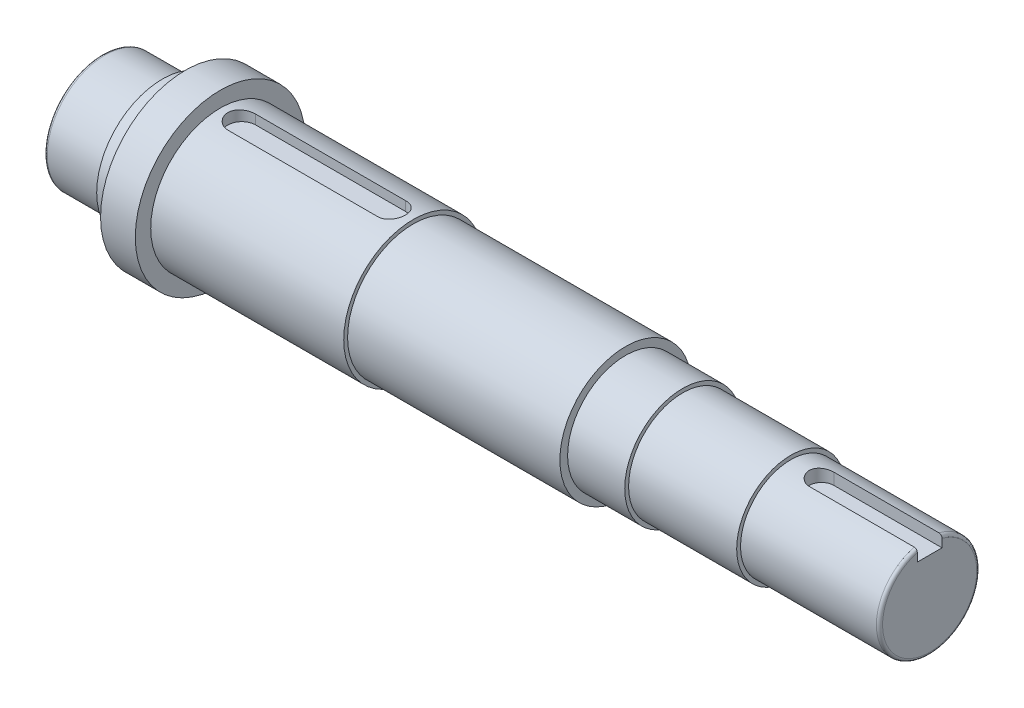
SolidWorks part; units mm, degrees
material "Plain Carbon Steel"
ref_plane "Front Plane" through (0, 0, 0) normal (0, 0, 1) x (1, 0, 0)
ref_plane "Top Plane" through (0, 0, 0) normal (0, 1, 0) x (1, 0, 0)
ref_plane "Right Plane" through (0, 0, 0) normal (1, 0, 0) x (0, 0, -1)
sketch "Sketch1" plane through (0, 0, 0) normal (0, 0, 1) x (1, 0, 0)
  line L0 (-305.229, 0) -> (230.771, 0) construction
  line L1 (-305.229, 0) -> (-305.229, 37.5)
  line L2 (-305.229, 37.5) -> (-266.229, 37.5)
  line L3 (-266.229, 37.5) -> (-266.229, 42.5)
  line L4 (-266.229, 42.5) -> (-251.229, 42.5)
  line L5 (-251.229, 42.5) -> (-251.229, 55)
  line L6 (-251.229, 55) -> (-228.729, 55)
  line L7 (-228.729, 55) -> (-228.729, 45)
  line L8 (-228.729, 45) -> (-103.729, 45)
  line L9 (-103.729, 45) -> (-103.729, 42.5)
  line L10 (-103.729, 42.5) -> (33.771, 42.5)
  line L11 (33.771, 42.5) -> (33.771, 37.5)
  line L12 (33.771, 37.5) -> (70.771, 37.5)
  line L13 (70.771, 37.5) -> (70.771, 35)
  line L14 (70.771, 35) -> (140.771, 35)
  line L15 (140.771, 35) -> (140.771, 32.5)
  line L16 (140.771, 32.5) -> (230.771, 32.5)
  line L17 (230.771, 32.5) -> (230.771, 0)
  line L18 (-305.229, 0) -> (230.771, 0)
  dimension "D1" = 75
  dimension "D2" = 85
  dimension "D3" = 110
  dimension "D4" = 90
  dimension "D5" = 85
  dimension "D6" = 75
  dimension "D7" = 70
  dimension "D8" = 65
  dimension "D9" = 39
  dimension "D10" = 15
  dimension "D11" = 22.5
  dimension "D12" = 125
  dimension "D13" = 137.5
  dimension "D14" = 37
  dimension "D15" = 70
  dimension "D16" = 90
  dimension "D17" = 305.229
  dimension "D18" = 536
revolve "Revolve1" add sketch "Sketch1" angle 360 about L0
fillet "Fillet1" radius 2 2 edges at (230.771, 0, 32.5) (-305.229, 0, 37.5)
ref_plane "Plane1" through (0, 45, 0) normal (0, 1, 0) x (1, 0, 0)
ref_plane "Plane2" through (0, 32.5, 0) normal (0, 1, 0) x (1, 0, 0)
sketch "Sketch2" plane through (0, 45, 0) normal (0, 1, 0) x (1, 0, 0)
  line L0 (-214.729, 0) -> (-117.729, 0) construction
  line L1 (-214.729, 9) -> (-117.729, 9)
  line L2 (-214.729, -9) -> (-117.729, -9)
  line L3 (-103.729, -45) -> (-103.729, 45) construction
  arc A0 (-214.729, 9) -> (-214.729, -9) centre (-214.729, 0) ccw
  arc A1 (-117.729, -9) -> (-117.729, 9) centre (-117.729, 0) ccw
  point P3 (-166.229, 0)
  dimension "D3" = 9
  dimension "D1" = 62.5
  dimension "D2" = 97
extrude "Cut-Extrude1" cut sketch "Sketch2" against normal blind 7
sketch "Sketch3" plane through (0, 32.5, 0) normal (0, 1, 0) x (1, 0, 0)
  line L0 (160.771, 0) -> (239.6722, 0) construction
  line L1 (160.771, 8) -> (239.6722, 8)
  line L2 (160.771, -8) -> (239.6722, -8)
  line L3 (230.771, -30.5) -> (230.771, 30.5) construction
  arc A0 (160.771, 8) -> (160.771, -8) centre (160.771, 0) ccw
  arc A1 (239.6722, -8) -> (239.6722, 8) centre (239.6722, 0) ccw
  point P3 (200.2216, 0)
  dimension "D2" = 8
  dimension "D1" = 70
extrude "Cut-Extrude2" cut sketch "Sketch3" against normal blind 8.42
